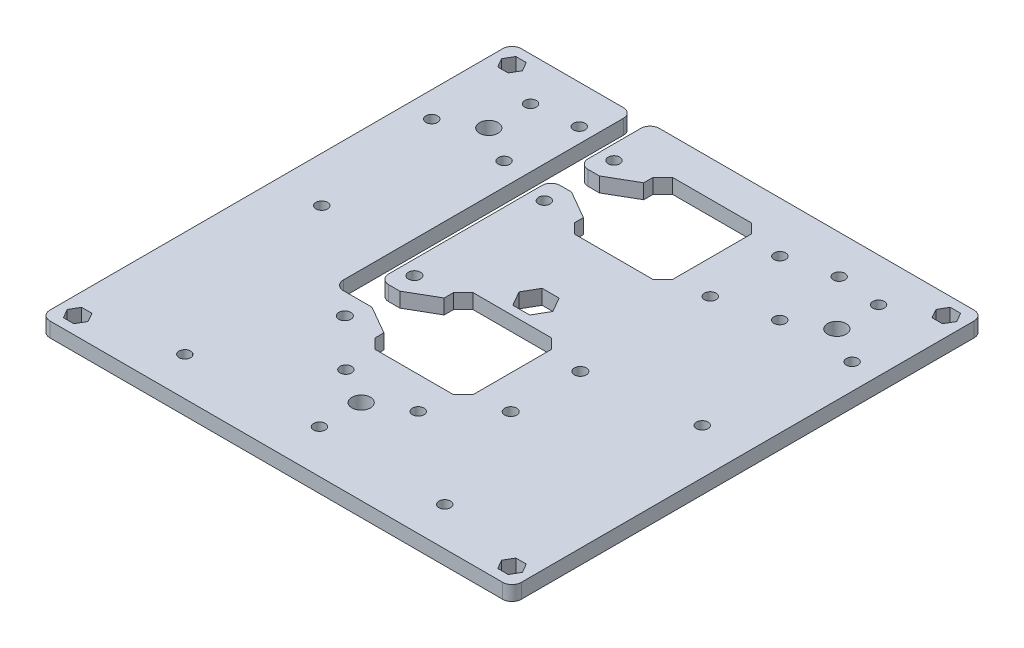
SolidWorks part; units mm, degrees
ref_plane "Plan de face" through (0, 0, 0) normal (0, 0, 1) x (1, 0, 0)
ref_plane "Plan de dessus" through (0, 0, 0) normal (0, 1, 0) x (1, 0, 0)
ref_plane "Plan de droite" through (0, 0, 0) normal (1, 0, 0) x (0, 0, -1)
sketch "Esquisse1" plane through (0, 0, 0) normal (0, 1, 0) x (1, 0, 0)
  line L1 (-101.6, -101.6) -> (101.6, -101.6)
  line L2 (-101.6, -101.6) -> (-101.6, 101.6)
  line L3 (-101.6, 101.6) -> (101.6, 101.6)
  line L4 (101.6, -101.6) -> (101.6, 101.6)
  line L5 (-101.6, -101.6) -> (101.6, 101.6) construction
  line L6 (-101.6, 101.6) -> (101.6, -101.6) construction
  point P0 (0, 0)
  dimension "D1" = 203.2
extrude "Boss.-Extru.1" add sketch "Esquisse1" along normal blind 6.35
sketch "Esquisse2" plane through (0, 6.35, 0) normal (0, 1, 0) x (1, 0, 0)
  circle A0 centre (-75, 65) radius 4
  circle A1 centre (75, 65) radius 4
  circle A2 centre (0, -65) radius 4
  dimension "D1" = 8
  dimension "D2" = 65
  dimension "D3" = 65
  dimension "D4" = 150
  dimension "D5" = 75
extrude "Enlèv. mat.-Extru.1" cut sketch "Esquisse2" against normal through all
sketch "Esquisse3" plane through (0, 6.35, 0) normal (0, 1, 0) x (1, 0, 0)
  line L0 (-16.9781, 86.15) -> (-21.15, 81.9781)
  line L1 (-21.15, 81.9781) -> (-21.15, 48.0219)
  line L2 (-21.15, 48.0219) -> (-16.9781, 43.85)
  line L3 (-16.9781, 43.85) -> (16.9781, 43.85)
  line L4 (16.9781, 43.85) -> (21.15, 48.0219)
  line L5 (21.15, 48.0219) -> (21.15, 81.9781)
  line L6 (21.15, 81.9781) -> (16.9781, 86.15)
  line L7 (16.9781, 86.15) -> (-16.9781, 86.15)
  line L9 (-75, 65) -> (75, 65) construction
  point P8 (0, 43.85)
  point P11 (0, 86.15)
  point P12 (-21.15, 65)
  point P13 (21.15, 65)
  dimension "D1" = 5.9
  dimension "D2" = 42.3
extrude "Enlèv. mat.-Extru.2" cut sketch "Esquisse3" against normal through all
sketch "Esquisse5" plane through (0, 6.35, 0) normal (0, 1, 0) x (1, 0, 0)
  circle A0 centre (-35.9, 49.85) radius 2.5
  circle A1 centre (-35.9, 79.85) radius 2.5
  circle A2 centre (35.6, 79.85) radius 2.5
  circle A3 centre (35.6, 49.85) radius 2.5
extrude "Enlèv. mat.-Extru.4" cut sketch "Esquisse5" against normal through all
sketch "Esquisse6" plane through (0, 6.35, 0) normal (0, 1, 0) x (1, 0, 0)
  circle A0 centre (93.6, -93.6) radius 2.5
  circle A1 centre (-93.6, -93.6) radius 2.5
  circle A2 centre (-93.6, 93.6) radius 2.5
  circle A3 centre (93.6, 93.6) radius 2.5
extrude "Enlèv. mat.-Extru.5" cut sketch "Esquisse6" against normal through all
sketch "Esquisse7" plane through (0, 6.35, 0) normal (0, 1, 0) x (1, 0, 0)
  line L0 (-97.6, -101.6) -> (97.6, -101.6) construction
  line L1 (-98.1033, -93.6) -> (-95.8517, -97.5)
  line L2 (-95.8517, -97.5) -> (-91.3483, -97.5)
  line L3 (-91.3483, -97.5) -> (-89.0967, -93.6)
  line L4 (-89.0967, -93.6) -> (-91.3483, -89.7)
  line L5 (-91.3483, -89.7) -> (-95.8517, -89.7)
  line L6 (-95.8517, -89.7) -> (-98.1033, -93.6)
  line L7 (89.0967, -93.6) -> (91.3483, -97.5)
  line L8 (91.3483, -97.5) -> (95.8517, -97.5)
  line L9 (95.8517, -97.5) -> (98.1033, -93.6)
  line L10 (98.1033, -93.6) -> (95.8517, -89.7)
  line L11 (95.8517, -89.7) -> (91.3483, -89.7)
  line L12 (91.3483, -89.7) -> (89.0967, -93.6)
  line L13 (89.0967, 93.6) -> (91.3483, 89.7)
  line L14 (91.3483, 89.7) -> (95.8517, 89.7)
  line L15 (95.8517, 89.7) -> (98.1033, 93.6)
  line L16 (98.1033, 93.6) -> (95.8517, 97.5)
  line L17 (95.8517, 97.5) -> (91.3483, 97.5)
  line L18 (91.3483, 97.5) -> (89.0967, 93.6)
  line L19 (-98.1033, 93.6) -> (-95.8517, 89.7)
  line L20 (-95.8517, 89.7) -> (-91.3483, 89.7)
  line L21 (-91.3483, 89.7) -> (-89.0967, 93.6)
  line L22 (-89.0967, 93.6) -> (-91.3483, 97.5)
  line L23 (-91.3483, 97.5) -> (-95.8517, 97.5)
  line L24 (-95.8517, 97.5) -> (-98.1033, 93.6)
  line L25 (97.6, 101.6) -> (-97.6, 101.6) construction
  circle A0 centre (-93.6, -93.6) radius 3.9 construction
  circle A1 centre (93.6, -93.6) radius 3.9 construction
  circle A2 centre (93.6, 93.6) radius 3.9 construction
  circle A3 centre (-93.6, 93.6) radius 3.9 construction
  dimension "D1" = 7.8
extrude "Enlèv. mat.-Extru.6" cut sketch "Esquisse7" against normal through all and the other way through all
sketch "Esquisse8" plane through (0, 6.35, 0) normal (0, 1, 0) x (1, 0, 0)
  circle A0 centre (90.5885, 56) radius 2.5
  circle A1 centre (59.4115, 56) radius 2.5
  circle A2 centre (75, 83) radius 2.5
  circle A3 centre (-90.5899, 55.9992) radius 2.5
  circle A4 centre (-75.0015, 82.9992) radius 2.5
  circle A5 centre (-59.413, 55.9992) radius 2.5
  circle A6 centre (-15.5885, -56) radius 2.5
  circle A7 centre (15.5885, -56) radius 2.5
  circle A8 centre (0, -83) radius 2.5
extrude "Enlèv. mat.-Extru.7" cut sketch "Esquisse8" against normal through all
sketch "Esquisse9" plane through (0, 6.35, 0) normal (0, 1, 0) x (1, 0, 0)
  line L0 (-101.6, -101.6) -> (101.6, -101.6) construction
  line L1 (-7.3035, 10.325) -> (-3.6517, 4)
  line L2 (-3.6517, 4) -> (3.6517, 4)
  line L3 (3.6517, 4) -> (7.3035, 10.325)
  line L4 (7.3035, 10.325) -> (3.6517, 16.65)
  line L5 (3.6517, 16.65) -> (-3.6517, 16.65)
  line L6 (-3.6517, 16.65) -> (-7.3035, 10.325)
  line L7 (3.6517, 16.65) -> (-3.6517, 16.65) construction
  line L8 (-7.3035, 10.325) -> (-3.6517, 4) construction
  circle A0 centre (0, 10.325) radius 6.325 construction
  dimension "D1" = 12.65
extrude "Enlèv. mat.-Extru.8" cut sketch "Esquisse9" against normal through all
sketch "Esquisse10" plane through (0, 0, 0) normal (0, -1, 0) x (1, 0, 0)
  circle A0 centre (56, -85) radius 2.5
  circle A1 centre (56, -85) radius 2.5 construction
  circle A2 centre (82, 0) radius 2.5
  circle A3 centre (82, 0) radius 2.5 construction
  circle A4 centre (56, 85) radius 2.5
  circle A5 centre (56, 85) radius 2.5 construction
extrude "Enlèv. mat.-Extru.9" cut sketch "Esquisse10" against normal through all
mirror "Symétrie1" about plane through (0, 0, 0) normal (1, 0, 0) of "Enlèv. mat.-Extru.9"
sketch "Esquisse13" plane through (0, 6.35, 0) normal (0, 1, 0) x (1, 0, 0)
  line L0 (16.9781, -42.15) -> (21.15, -37.9781)
  line L1 (21.15, -37.9781) -> (21.15, -4.0219)
  line L2 (21.15, -4.0219) -> (16.9781, 0.15)
  line L3 (16.9781, 0.15) -> (-16.9781, 0.15)
  line L4 (-16.9781, 0.15) -> (-21.15, -4.0219)
  line L5 (-21.15, -4.0219) -> (-21.15, -37.9781)
  line L6 (-21.15, -37.9781) -> (-16.9781, -42.15)
  line L7 (-16.9781, -42.15) -> (16.9781, -42.15)
  line L8 (16.9781, -42.15) -> (21.15, -37.9781) construction
  line L9 (21.15, -37.9781) -> (21.15, -4.0219) construction
  line L10 (-16.9781, -42.15) -> (16.9781, -42.15) construction
  line L11 (-21.15, -37.9781) -> (-16.9781, -42.15) construction
extrude "Enlèv. mat.-Extru.11" cut sketch "Esquisse13" against normal through all
sketch "Esquisse11" plane through (0, 6.35, 0) normal (0, 1, 0) x (1, 0, 0)
  line L0 (-21.15, 81.9781) -> (-21.15, 48.0219) construction
  line L1 (-21.15, 58.9281) -> (-42.1, 58.9281)
  line L2 (-21.15, 58.9281) -> (-21.15, 70.9281)
  line L3 (-21.15, 70.9281) -> (-42.1, 70.9281)
  line L5 (101.6, 101.6) -> (-101.6, 101.6) construction
  line L7 (-49.6, 58.9281) -> (-49.6, 101.6)
  line L8 (-49.6, 101.6) -> (-42.1, 101.6)
  line L9 (-42.1, 70.9281) -> (-42.1, 101.6)
  line L10 (-101.6, 101.6) -> (-101.6, -101.6) construction
  line L11 (-21.15, -4.0219) -> (-21.15, -37.9781) construction
  line L13 (-49.6, 58.9281) -> (-49.6, -15.0719)
  line L15 (-42.1, 58.9281) -> (-42.1, -15.0719)
  line L16 (-42.1, -15.0719) -> (-21.15, -15.0719)
  line L17 (-49.6, -15.0719) -> (-49.6, -27.0719)
  line L18 (-49.6, -27.0719) -> (-21.15, -27.0719)
  line L19 (-21.15, -15.0719) -> (-21.15, -27.0719)
  dimension "D1" = 7.5
  dimension "D2" = 12
  dimension "D3" = 11.05
  dimension "D4" = 52
  dimension "D5" = 11.05
extrude "Enlèv. mat.-Extru.10" cut sketch "Esquisse11" against normal through all
fillet "Congé1" radius 4 10 edges at (-42.1, 3.175, -101.6) (-49.6, 3.175, -101.6) (-42.1, 3.175, -70.9281) (-101.6, 3.175, 101.6) (101.6, 3.175, 101.6) (101.6, 3.175, -101.6) (-101.6, 3.175, -101.6) (-49.6, 3.175, 27.0719) (-42.1, 3.175, 15.0719) (-42.1, 3.175, -58.9281)
sketch "Esquisse16" plane through (0, 6.35, 0) normal (0, 1, 0) x (1, 0, 0)
  circle A0 centre (35.6, -36.15) radius 2.6
  circle A1 centre (35.6, -6.15) radius 2.6
  circle A2 centre (-35.9, -6.15) radius 2.6
  circle A3 centre (-35.9, -36.15) radius 2.6
  circle A4 centre (35.6, -36.15) radius 2.6 construction
extrude "Enlèv. mat.-Extru.12" cut sketch "Esquisse16" against normal through all
chamfer "Chanfrein1" distance 7 angle 60 2 edges at (-21.15, 3.175, -58.9281) (-21.15, 3.175, -70.9281)
chamfer "Chanfrein2" distance 7 angle 60 2 edges at (-21.15, 3.175, 27.0719) (-21.15, 3.175, 15.0719)
